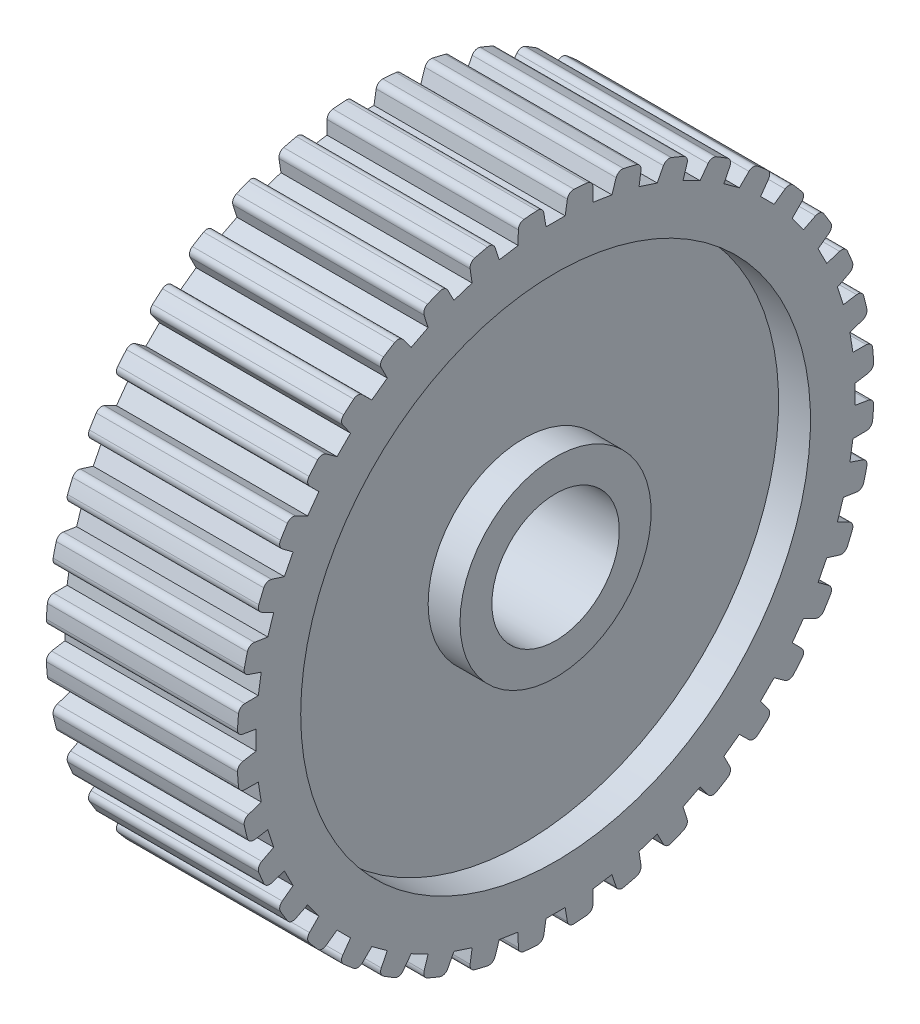
SolidWorks part; units mm, degrees
material "PTFE (general)"
ref_plane "Front Plane" through (0, 0, 0) normal (0, 0, 1) x (1, 0, 0)
ref_plane "Top Plane" through (0, 0, 0) normal (0, 1, 0) x (1, 0, 0)
ref_plane "Right Plane" through (0, 0, 0) normal (1, 0, 0) x (0, 0, -1)
sketch "Sketch1" plane through (0, 0, 0) normal (0, 0, 1) x (1, 0, 0)
  line L0 (-99.3162, 0) -> (118.1197, 0) construction
  line L1 (-15, 10) -> (15, 10)
  line L2 (15, 10) -> (15, 15)
  line L3 (15, 15) -> (10, 15)
  line L4 (10, 15) -> (10, 40)
  line L5 (10, 40) -> (15, 40)
  line L6 (15, 40) -> (15, 50)
  line L7 (15, 50) -> (-15, 50)
  line L8 (-15, 50) -> (-15, 40)
  line L9 (-15, 40) -> (-10, 40)
  line L10 (-10, 40) -> (-10, 15)
  line L11 (-10, 15) -> (-15, 15)
  line L12 (-15, 15) -> (-15, 10)
  point P19 (0, 10)
  dimension "D1" = 10
  dimension "D2" = 50
  dimension "D3" = 30
  dimension "D4" = 20
  dimension "D5" = 5
  dimension "D6" = 10
revolve "Revolve1" add sketch "Sketch1" angle 360 about L0
sketch "Sketch2" plane through (15, 0, 0) normal (1, 0, 0) x (0, 0, -1)
  line L0 (-2.5, 53) -> (2.5, 53)
  line L1 (2.5, 53) -> (1.5, 47)
  line L2 (1.5, 47) -> (-1.5, 47)
  line L3 (-1.5, 47) -> (-2.5, 53)
  circle A0 centre (0, 0) radius 50 construction
  point P2 (0, 47)
  point P6 (0, 53)
  point P7 (0, 50)
  dimension "D1" = 3
  dimension "D2" = 5
  dimension "D3" = 6
  dimension "D4" = 3
extrude "Cut-Extrude1" cut sketch "Sketch2" against normal through all both and the other way through all
fillet "Fillet1" radius 1 2 edges at (0, 49.9602, 1.9934) (0, 49.9602, -1.9934)
pattern_circular "CirPattern1" count 40 over 360 about axis through (0, 0, 0) along (1, 0, 0) of "Fillet1", "Cut-Extrude1"
